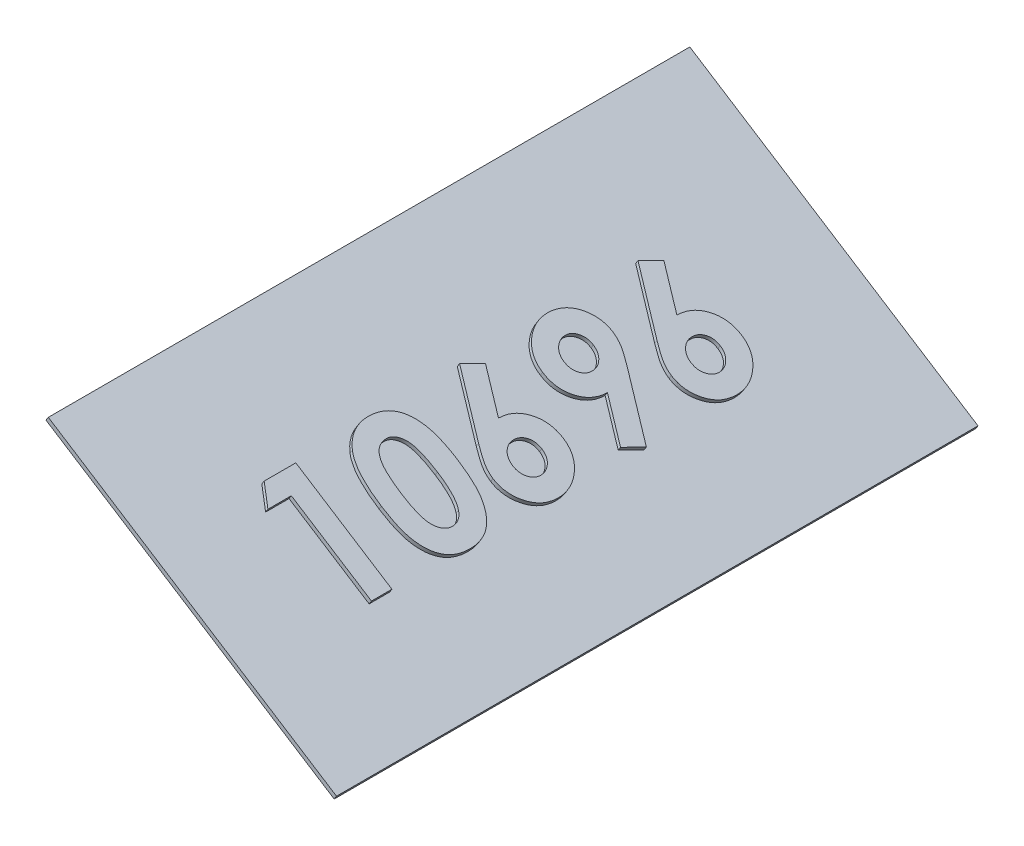
SolidWorks part; units mm, degrees
material "ABS PC"
ref_plane "Front Plane" through (0, 0, 0) normal (0, 0, 1) x (1, 0, 0)
ref_plane "Top Plane" through (0, 0, 0) normal (0, 1, 0) x (1, 0, 0)
ref_plane "Right Plane" through (0, 0, 0) normal (1, 0, 0) x (0, 0, -1)
sketch "Sketch1" plane through (0, 0, 0) normal (0, 0, 1) x (1, 0, 0)
  line L0 (-701.8113, 261.5839) -> (-534.693, 154.8651)
extrude "Extrude-Thin1" add sketch "Sketch1" along normal blind 372 thin contours L0
sketch "Sketch3" plane through (-84.6341, -132.5344, 0) normal (0.5382, 0.8428, 0) x (0.8428, -0.5382, 0)
  text T0 "  10696" font "Century Gothic" height in points 250
extrude "Boss-Extrude1" add sketch "Sketch3" along normal blind 2.5
